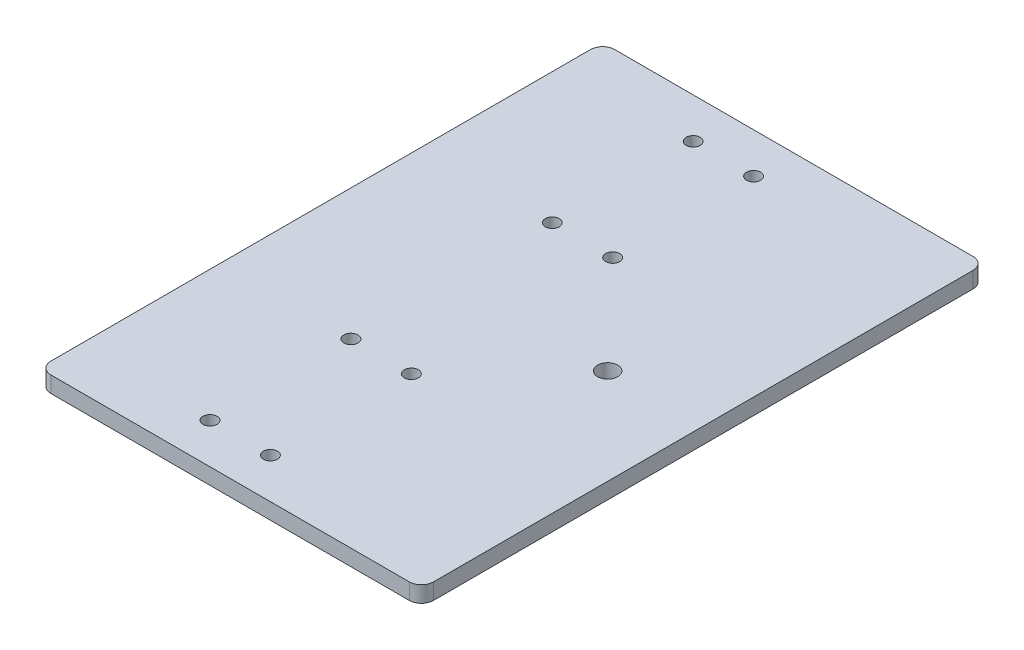
SolidWorks part; units mm, degrees
ref_plane "Front Plane" through (0, 0, 0) normal (0, 0, 1) x (1, 0, 0)
ref_plane "Top Plane" through (0, 0, 0) normal (0, 1, 0) x (1, 0, 0)
ref_plane "Right Plane" through (0, 0, 0) normal (1, 0, 0) x (0, 0, -1)
sketch "Sketch1" plane through (0, 0, 0) normal (0, 1, 0) x (1, 0, 0)
  line L0 (0, -2.2) -> (0, 2.2) construction
  line L1 (-47.5, 70) -> (47.5, 70)
  line L2 (-47.5, 70) -> (-47.5, -70)
  line L3 (-47.5, -70) -> (47.5, -70)
  line L4 (47.5, 70) -> (47.5, -70)
  line L5 (-47.5, 70) -> (47.5, -70) construction
  line L6 (-47.5, -70) -> (47.5, 70) construction
  line L7 (-2.2, 0) -> (2.2, 0) construction
  circle A0 centre (0, 60) radius 1.75
  circle A1 centre (0, 25) radius 1.75
  circle A2 centre (0, -25) radius 1.75
  circle A3 centre (0, -60) radius 1.75
  circle A4 centre (-15, 60) radius 1.75
  circle A5 centre (-15, 25) radius 1.75
  circle A6 centre (-15, -25) radius 1.75
  circle A7 centre (-15, -60) radius 1.75
  circle A8 centre (23.75, 0) radius 2.5
  point P0 (0, 0)
  dimension "D3" = 3.5
  dimension "D9" = 5
  dimension "D1" = 95
  dimension "D2" = 140
  dimension "D4" = 10
  dimension "D6" = 35
  dimension "D8" = 15
  dimension "D10" = 23.75
  dimension "D5" = 2
  dimension "D7" = 2
extrude "Boss-Extrude1" add sketch "Sketch1" along normal blind 4
fillet "Fillet1" radius 3 4 edges at (-47.5, 2, -70) (47.5, 2, -70) (47.5, 2, 70) (-47.5, 2, 70)
